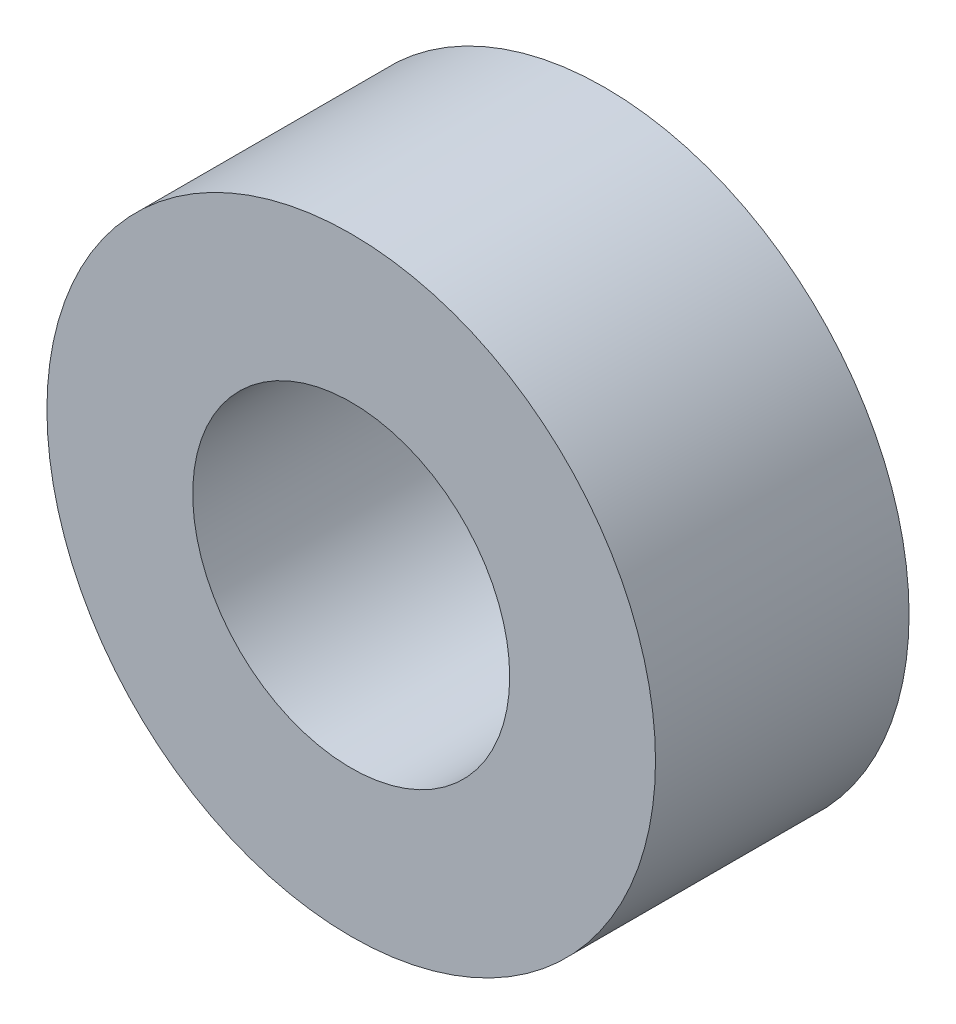
SolidWorks part; units mm, degrees
ref_plane "Front Plane" through (0, 0, 0) normal (0, 0, 1) x (1, 0, 0)
ref_plane "Top Plane" through (0, 0, 0) normal (0, 1, 0) x (1, 0, 0)
ref_plane "Right Plane" through (0, 0, 0) normal (1, 0, 0) x (0, 0, -1)
sketch "Sketch1" plane through (0, 0, 0) normal (0, 0, 1) x (1, 0, 0)
  circle A0 centre (0, 0) radius 6
  circle A1 centre (0, 0) radius 3.125
  dimension "D1" = 12
  dimension "D2" = 6.25
extrude "Boss-Extrude1" add sketch "Sketch1" along normal mid plane 5
